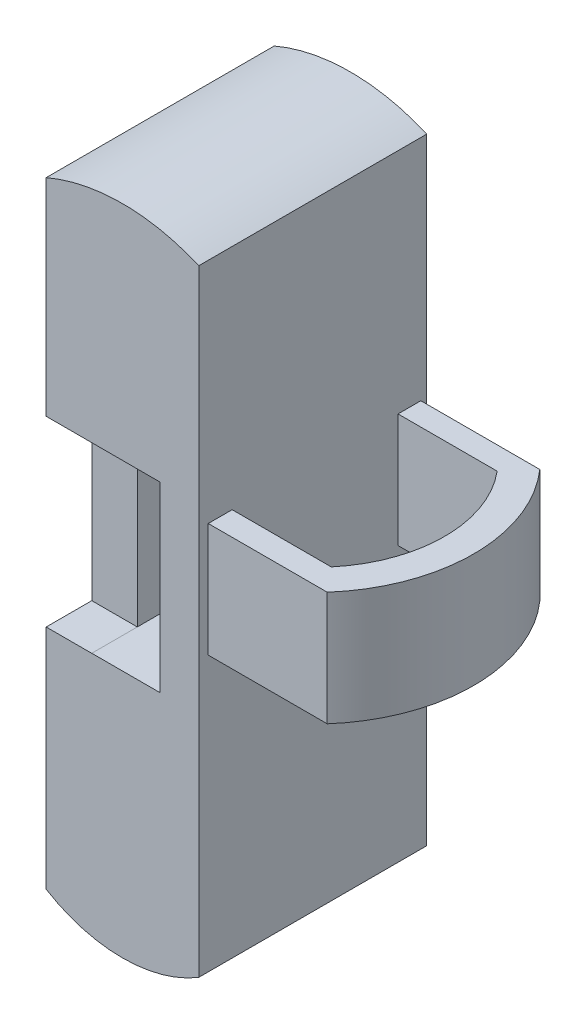
SolidWorks part; units mm, degrees
ref_plane "前基準面" through (0, 0, 0) normal (0, 0, 1) x (1, 0, 0)
ref_plane "上基準面" through (0, 0, 0) normal (0, 1, 0) x (1, 0, 0)
ref_plane "右基準面" through (0, 0, 0) normal (1, 0, 0) x (0, 0, -1)
sketch "草圖1" plane through (0, 0, 0) normal (0, 0, 1) x (1, 0, 0)
  line L0 (0, 0) -> (0, -27.0335)
  line L1 (6.6927, 0) -> (6.6927, -27.0335)
  arc A0 (6.6927, 0) -> (0, 0) centre (3.3464, -7.7736) ccw
  arc A1 (6.6927, -27.0335) -> (0, -27.0335) centre (3.3464, -21.5123) cw
  point P7 (0, 0)
  point P8 (0, 0)
extrude "填料-伸長1" add sketch "草圖1" along normal blind 10 contours L0 A1 L1 A0
sketch "草圖3" plane through (0, 0, 10) normal (0, 0, 1) x (1, 0, 0)
  line L2 (5, -9.0672) -> (2, -9.0672)
  line L3 (5, -9.0672) -> (5, -17.0672)
  line L4 (5, -17.0672) -> (2, -17.0672)
  line L5 (2, -9.0672) -> (2, -17.0672)
  point P2 (0, 0)
  point P9 (0, 0)
extrude "除料-伸長2" cut sketch "草圖3" against normal blind 10 contours L2 L5 L4 L3
ref_plane "平面1" through (0, -12.5, 0) normal (0, 1, 0) x (1, 0, 0)
sketch "草圖4" plane through (0, -12.5, -0.0926) normal (0, 1, 0) x (1, 0, 0)
  line L0 (6.3087, -9.6764) -> (11.9124, -9.6764)
  line L1 (6.3087, -0.3519) -> (11.9124, -0.3519)
  line L2 (6.3087, -9.6764) -> (6.3087, -0.3519)
  arc A0 (11.9124, -9.6764) -> (11.9124, -0.3519) centre (6.6191, -5.0142) ccw
  point P4 (14.1741, -0.2532)
  point P6 (6.6853, 0)
  point P7 (13.3087, 0)
  point P8 (0, 0)
  point P9 (14.1741, -10.0979)
  point P10 (11.9124, -0.3519)
  point P11 (11.9124, -9.6764)
extrude "填料-伸長2" add sketch "草圖4" along normal mid plane 5 contours A0 L1 L2 L0
sketch "草圖6" plane through (0, -10, 0) normal (0, 1, 0) x (1, 0, 0)
  line L0 (7.8546, -9.5838) -> (7.8546, -8.5353)
  line L1 (6.6927, -9.5838) -> (11.9124, -9.5838) construction
  line L2 (8.9341, -0.2593) -> (8.9341, -1.2593)
  line L3 (6.6927, -0.2593) -> (11.9124, -0.2593) construction
  line L4 (6.6927, -8.5353) -> (11.0392, -8.5353)
  line L5 (6.6927, -0.2593) -> (6.6927, -9.5838) construction
  line L6 (6.6927, -1.2593) -> (11.0392, -1.2593)
  line L7 (6.6927, -8.5353) -> (6.6927, -1.2593)
  arc A0 (11.0392, -1.2593) -> (11.0392, -8.5353) centre (6.7327, -4.8973) cw
  point P14 (11.0392, -1.1633)
  point P16 (11.0392, -8.4393)
extrude "除料-伸長3" cut sketch "草圖6" against normal blind 5 contours L4 A0 L6 L7
sketch "草圖7" plane through (0, 0, 0) normal (0, 0, -1) x (-1, 0, 0)
  line L0 (0, 0) -> (0, -27.0335) construction
  line L1 (-2, -9.0672) -> (0, -9.0672)
  line L2 (-2, -9.0672) -> (-2, -17.0677)
  line L3 (-2, -17.0677) -> (0, -17.0677)
  line L4 (0, -9.0672) -> (0, -17.0677)
extrude "除料-伸長4" cut sketch "草圖7" against normal blind 2 contours L1 L4 L3 L2
sketch "草圖8" plane through (0, 0, 10) normal (0, 0, 1) x (1, 0, 0)
  line L0 (0, 0) -> (0, -27.0335) construction
  line L1 (2, -9.0672) -> (0, -9.0672)
  line L2 (2, -9.0672) -> (2, -17.0694)
  line L3 (2, -17.0694) -> (0, -17.0694)
  line L4 (0, -9.0672) -> (0, -17.0694)
extrude "除料-伸長5" cut sketch "草圖8" against normal blind 2 contours L3 L4 L1 L2
